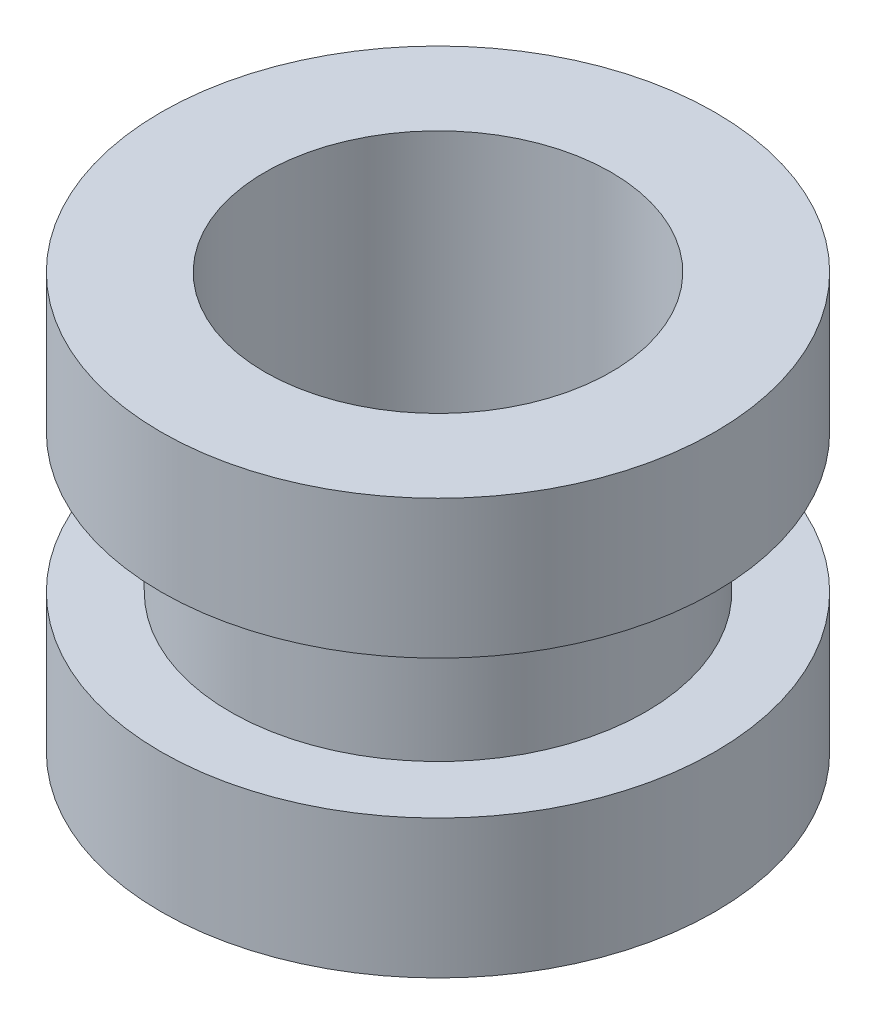
SolidWorks part; units mm, degrees
ref_plane "Front Plane" through (0, 0, 0) normal (0, 0, 1) x (1, 0, 0)
ref_plane "Top Plane" through (0, 0, 0) normal (0, 1, 0) x (1, 0, 0)
ref_plane "Right Plane" through (0, 0, 0) normal (1, 0, 0) x (0, 0, -1)
sketch "Sketch1" plane through (0, 0, 0) normal (0, 0, 1) x (1, 0, 0)
  line L0 (3.81, 3.81) -> (0, 3.81) construction
  line L1 (0, 0) -> (5.08, 0)
  line L2 (0, 0) -> (0, 7.62)
  line L3 (0, 7.62) -> (5.08, 7.62)
  line L4 (5.08, 0) -> (5.08, 2.54)
  line L5 (5.08, 5.08) -> (3.81, 5.08)
  line L6 (3.81, 5.08) -> (3.81, 2.54)
  line L7 (5.08, 2.54) -> (3.81, 2.54)
  line L8 (5.08, 5.08) -> (5.08, 7.62)
  point P11 (3.81, 3.81)
  dimension "D1" = 7.62
  dimension "D2" = 5.08
  dimension "D3" = 1.27
  dimension "D4" = 1.27
revolve "Revolve1" add sketch "Sketch1" angle 360 about L2
sketch "Sketch2" plane through (0, 7.62, 0) normal (0, 1, 0) x (1, 0, 0)
  circle A0 centre (0, 0) radius 3.175
  dimension "D1" = 6.35
extrude "Cut-Extrude1" cut sketch "Sketch2" against normal through all
